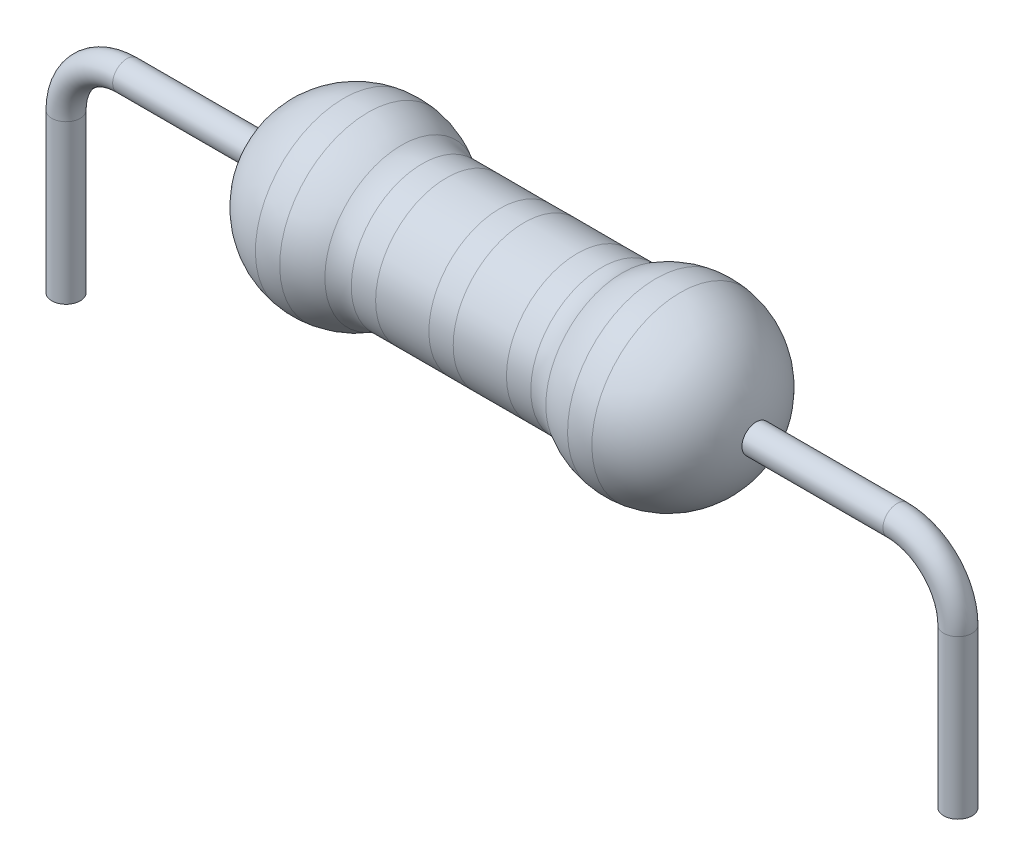
SolidWorks part; units mm, degrees
ref_plane "Front Plane" through (0, 0, 0) normal (0, 0, 1) x (1, 0, 0)
ref_plane "Top Plane" through (0, 0, 0) normal (0, 1, 0) x (1, 0, 0)
ref_plane "Right Plane" through (0, 0, 0) normal (1, 0, 0) x (0, 0, -1)
sketch "Sketch1" plane through (0, 0, 0) normal (0, 0, 1) x (1, 0, 0)
  line L0 (-3.025, 0) -> (3.025, 0) construction
  line L1 (-1.1068, 0.875) -> (1.1068, 0.875)
  line L2 (0, 0) -> (0, 0.875) construction
  line L3 (-3.025, 0) -> (3.025, 0)
  arc A0 (-1.3625, 0.9453) -> (-3.025, 0) centre (-1.925, 0) ccw
  arc A1 (-1.3625, 0.9453) -> (-1.1068, 0.875) centre (-1.1068, 1.375) ccw
  arc A2 (1.3625, 0.9453) -> (1.1068, 0.875) centre (1.1068, 1.375) cw
  arc A3 (1.3625, 0.9453) -> (3.025, 0) centre (1.925, 0) cw
  point P3 (0, 0)
  dimension "D3" = 2.2
  dimension "D4" = 1
  dimension "D1" = 6.05
  dimension "D2" = 0.875
revolve "Revolve1" add sketch "Sketch1" angle 360 about L3
sketch "Sketch2" plane through (0, 0, 0) normal (0, 1, 0) x (1, 0, 0)
  line L0 (-1.925, 1.1) -> (-1.925, -1.1) construction
  line L1 (-2.075, 1.5) -> (-1.775, 1.5)
  line L2 (-2.075, 1.5) -> (-2.075, -1.5)
  line L3 (-2.075, -1.5) -> (-1.775, -1.5)
  line L4 (-1.775, 1.5) -> (-1.775, -1.5)
  line L5 (0, 0) -> (0, 1.1542) construction
  line L6 (1.775, 1.5) -> (1.775, -1.5)
  line L7 (2.075, -1.5) -> (1.775, -1.5)
  line L8 (2.075, 1.5) -> (2.075, -1.5)
  line L9 (2.075, 1.5) -> (1.775, 1.5)
  line L10 (-1.1068, -0.875) -> (-1.1068, 0.875) construction
  line L11 (-1.1068, 1.5) -> (-0.8068, 1.5)
  line L12 (-1.1068, 1.5) -> (-1.1068, -1.5)
  line L13 (-1.1068, -1.5) -> (-0.8068, -1.5)
  line L14 (-0.8068, 1.5) -> (-0.8068, -1.5)
  line L15 (0.8068, 1.5) -> (0.8068, -1.5)
  line L16 (1.1068, -1.5) -> (0.8068, -1.5)
  line L17 (1.1068, 1.5) -> (1.1068, -1.5)
  line L18 (1.1068, 1.5) -> (0.8068, 1.5)
  line L20 (-0.15, -1.5) -> (0.15, -1.5)
  line L21 (-0.15, -1.5) -> (-0.15, 1.5)
  line L22 (-0.15, 1.5) -> (0.15, 1.5)
  line L23 (0.15, -1.5) -> (0.15, 1.5)
  line L24 (-0.15, -1.5) -> (0.15, 1.5) construction
  line L25 (-0.15, 1.5) -> (0.15, -1.5) construction
  arc A0 (-1.3625, 0.9453) -> (-1.3625, -0.9453) centre (-1.925, 0) ccw construction
  point P10 (-1.925, 1.5)
  point P11 (-1.775, 0)
  dimension "D1" = 0.3
  dimension "D2" = 3
split line "Split Line1"
sketch "Sketch4" plane through (0, 0, 0) normal (0, 1, 0) x (1, 0, 0)
  line L0 (0, 0) -> (0, 1.2166) construction
  line L1 (-3.039, -0.175) -> (-3.011, -0.175)
  line L2 (-3.039, -0.175) -> (-3.039, 0.175)
  line L3 (-3.039, 0.175) -> (-3.011, 0.175)
  line L4 (-3.011, -0.175) -> (-3.011, 0.175)
  line L5 (-3.039, -0.175) -> (-3.011, 0.175) construction
  line L6 (-3.039, 0.175) -> (-3.011, -0.175) construction
  line L7 (3.039, 0.175) -> (3.011, -0.175) construction
  line L8 (3.039, -0.175) -> (3.011, 0.175) construction
  line L9 (3.011, -0.175) -> (3.011, 0.175)
  line L10 (3.039, 0.175) -> (3.011, 0.175)
  line L11 (3.039, -0.175) -> (3.039, 0.175)
  line L12 (3.039, -0.175) -> (3.011, -0.175)
  arc A0 (-2.075, 1.0897) -> (-2.075, -1.0897) centre (-1.925, 0) ccw construction
  point P0 (-3.025, 0)
  point P15 (3.025, 0)
  dimension "D1" = 0.35
extrude "Cut-Extrude1" cut sketch "Sketch4" against normal through all both and the other way through all
sketch "Sketch7" plane through (0, 0, 0) normal (0, 0, 1) x (1, 0, 0)
  line L0 (-3.011, 0) -> (3.011, 0)
  line L1 (-3.011, 0.175) -> (-3.011, -0.175) construction
  line L2 (3.011, -0.175) -> (3.011, 0.175) construction
  line L3 (3.011, 0) -> (4.75, 0)
  line L4 (5.5, -0.75) -> (5.5, -8.7)
  line L5 (-4.75, 0) -> (-3.011, 0)
  line L6 (-5.5, -0.75) -> (-5.5, -8.7)
  arc A0 (5.5, -0.75) -> (4.75, 0) centre (4.75, -0.75) ccw
  arc A1 (-5.5, -0.75) -> (-4.75, 0) centre (-4.75, -0.75) cw
  point P13 (5.5, 0)
  dimension "D3" = 0.75
  dimension "D5" = 0.75
  dimension "D1" = 11
  dimension "D2" = 8.7
ref_plane "Plane1" through (-5.5, -8.7, 0) normal (0, 1, 0) x (1, 0, 0)
sketch "Sketch9" plane through (-5.5, -8.7, 0) normal (0, 1, 0) x (1, 0, 0)
  line L0 (0, 0) -> (0.75, 0) construction
  circle A0 centre (0, 0) radius 0.175
  dimension "D1" = 0.35
sweep "Sweep4" add profiles "Sketch9" path "Sketch7"
sketch "Croquis1" plane through (0, -8.7, 0) normal (0, -1, 0) x (1, 0, 0)
  line L1 (10, 10) -> (-10, 10)
  line L2 (10, 10) -> (10, -10)
  line L3 (10, -10) -> (-10, -10)
  line L4 (-10, 10) -> (-10, -10)
  line L5 (10, 10) -> (-10, -10) construction
  line L6 (10, -10) -> (-10, 10) construction
  point P0 (0, 0)
  dimension "D1" = 20
extrude "Cortar-Extruir1" cut sketch "Croquis1" against normal blind 6
